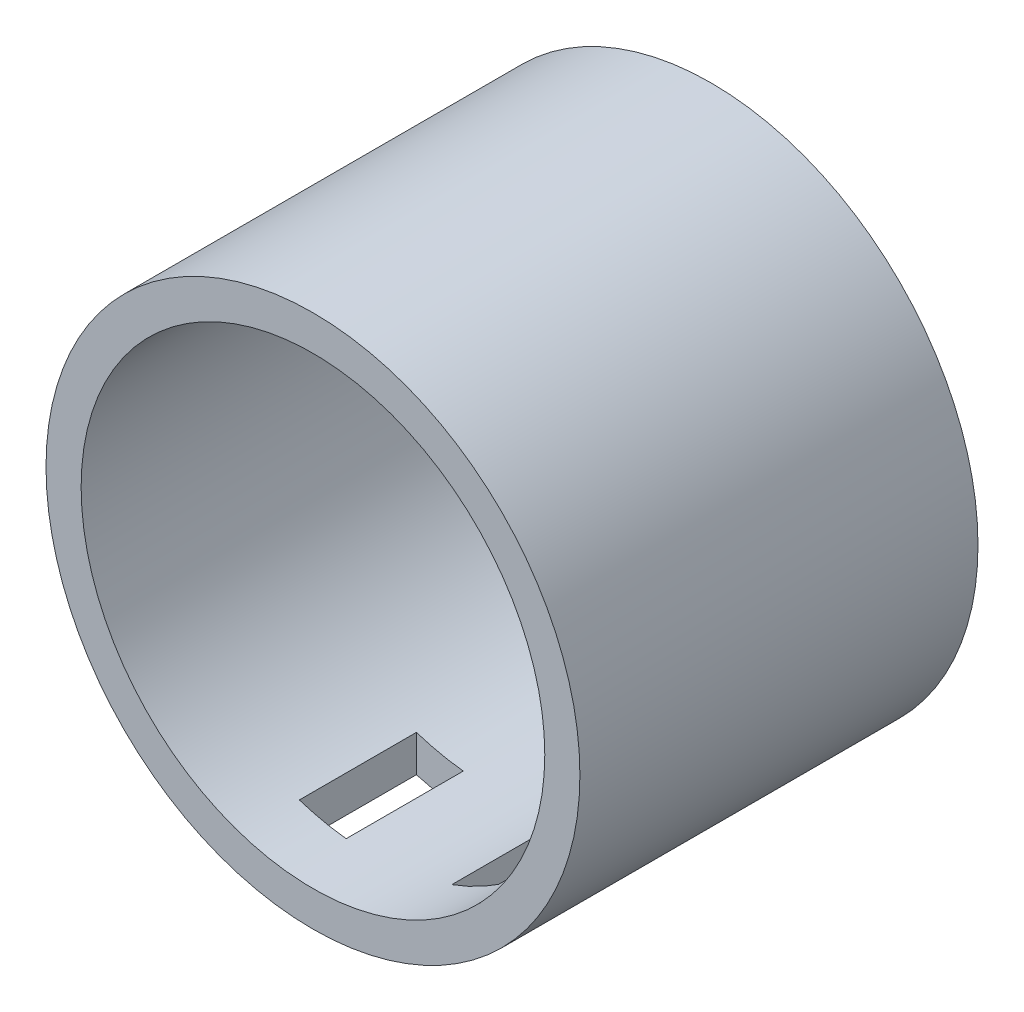
SolidWorks part; units mm, degrees
ref_plane "Plan de face" through (0, 0, 0) normal (0, 0, 1) x (1, 0, 0)
ref_plane "Plan de dessus" through (0, 0, 0) normal (0, 1, 0) x (1, 0, 0)
ref_plane "Plan de droite" through (0, 0, 0) normal (1, 0, 0) x (0, 0, -1)
sketch "Esquisse1" plane through (0, 0, 0) normal (0, 0, 1) x (1, 0, 0)
  circle A0 centre (0, 0) radius 9.9
  circle A1 centre (0, 0) radius 11.4
  dimension "D1" = 19.8
  dimension "D2" = 22.8
extrude "Boss.-Extru.1" add sketch "Esquisse1" along normal blind 15
sketch "Esquisse2" plane through (0, 0, 0) normal (0, 0, -1) x (-1, 0, 0)
  circle A0 centre (0, 0) radius 11.4
  circle A1 centre (0, 0) radius 2.5
  dimension "D1" = 22.8
  dimension "D2" = 5
extrude "Boss.-Extru.2" add sketch "Esquisse2" along normal blind 2
sketch "Esquisse3" plane through (0, 0, 0) normal (0, 1, 0) x (1, 0, 0)
  line L1 (5.4313, -12.503) -> (3.4313, -12.503)
  line L2 (5.4313, -12.503) -> (5.4313, -7.503)
  line L3 (5.4313, -7.503) -> (3.4313, -7.503)
  line L4 (3.4313, -12.503) -> (3.4313, -7.503)
  line L5 (-1.0787, -12.503) -> (-3.0787, -12.503)
  line L6 (-1.0787, -12.503) -> (-1.0787, -7.503)
  line L7 (-1.0787, -7.503) -> (-3.0787, -7.503)
  line L8 (-3.0787, -12.503) -> (-3.0787, -7.503)
  dimension "D1" = 2
  dimension "D2" = 2
  dimension "D3" = 5
  dimension "D4" = 5
extrude "Enlèv. mat.-Extru.1" cut sketch "Esquisse3" against normal blind 21
